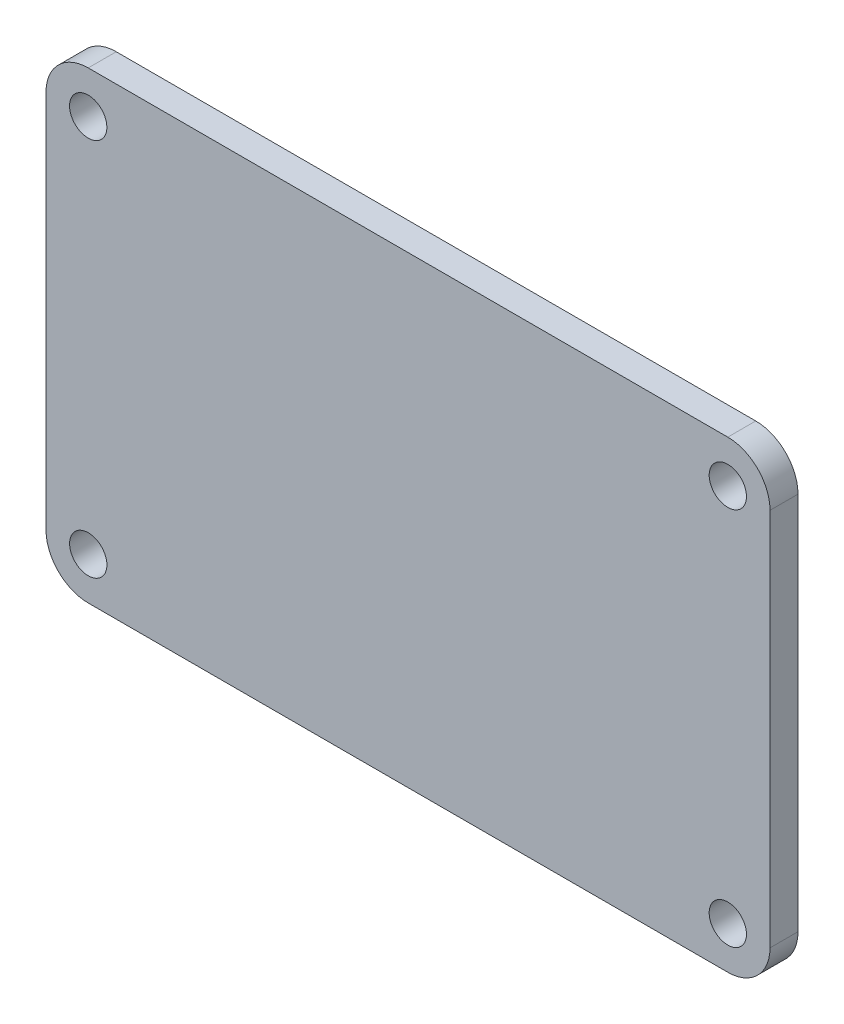
SolidWorks part; units mm, degrees
ref_plane "前视基准面" through (0, 0, 0) normal (0, 0, 1) x (1, 0, 0)
ref_plane "上视基准面" through (0, 0, 0) normal (0, 1, 0) x (1, 0, 0)
ref_plane "右视基准面" through (0, 0, 0) normal (1, 0, 0) x (0, 0, -1)
sketch "草图1" plane through (0, 0, 0) normal (0, 0, 1) x (1, 0, 0)
  line L0 (-34.285, 24.845) -> (34.285, 24.845)
  line L1 (-34.285, 22.845) -> (34.285, 22.845) construction
  line L2 (-36.815, 20.315) -> (-36.815, -20.315) construction
  line L3 (-34.285, -22.845) -> (34.285, -22.845) construction
  line L4 (36.815, 20.315) -> (36.815, -20.315) construction
  line L5 (-36.815, 22.845) -> (36.815, -22.845) construction
  line L6 (-36.815, -22.845) -> (36.815, 22.845) construction
  line L7 (-34.29, 20.32) -> (34.29, 20.32) construction
  line L8 (-34.29, 20.32) -> (-34.29, -20.32) construction
  line L9 (-34.29, -20.32) -> (34.29, -20.32) construction
  line L10 (34.29, 20.32) -> (34.29, -20.32) construction
  line L11 (-34.29, 20.32) -> (34.29, -20.32) construction
  line L12 (-34.29, -20.32) -> (34.29, 20.32) construction
  line L13 (38.815, 20.315) -> (38.815, -20.315)
  line L14 (-34.285, -24.845) -> (34.285, -24.845)
  line L15 (-38.815, 20.315) -> (-38.815, -20.315)
  arc A0 (-36.815, -20.315) -> (-34.285, -22.845) centre (-34.285, -20.315) ccw construction
  arc A1 (34.285, -22.845) -> (36.815, -20.315) centre (34.285, -20.315) ccw construction
  arc A2 (36.815, 20.315) -> (34.285, 22.845) centre (34.285, 20.315) ccw construction
  arc A3 (-36.815, 20.315) -> (-34.285, 22.845) centre (-34.285, 20.315) cw construction
  circle A4 centre (34.29, 20.32) radius 2
  circle A5 centre (34.29, -20.32) radius 2
  circle A6 centre (-34.29, 20.32) radius 2
  circle A7 centre (-34.285, -20.315) radius 2
  arc A8 (38.815, 20.315) -> (34.285, 24.845) centre (34.285, 20.315) ccw
  arc A9 (34.285, -24.845) -> (38.815, -20.315) centre (34.285, -20.315) ccw
  arc A10 (-38.815, -20.315) -> (-34.285, -24.845) centre (-34.285, -20.315) ccw
  arc A11 (-38.815, 20.315) -> (-34.285, 24.845) centre (-34.285, 20.315) cw
  point P0 (0, 0)
  point P18 (0, 0)
  dimension "D3" = 2.53
  dimension "D6" = 4
  dimension "D7" = 4
  dimension "D8" = 4
  dimension "D9" = 4
  dimension "D1" = 73.63
  dimension "D2" = 45.69
  dimension "D4" = 68.58
  dimension "D5" = 40.64
  dimension "D10" = 2
extrude "凸台-拉伸1" add sketch "草图1" along normal mid plane 3
